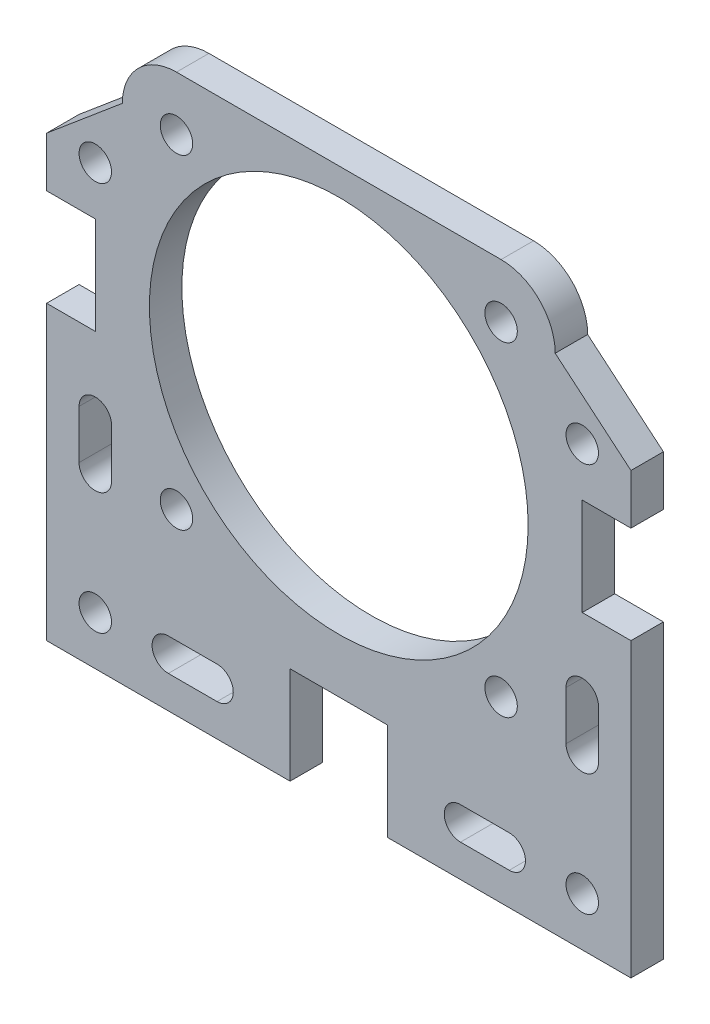
SolidWorks part; units mm, degrees
ref_plane "Alzado" through (0, 0, 0) normal (0, 0, 1) x (1, 0, 0)
ref_plane "Planta" through (0, 0, 0) normal (0, 1, 0) x (1, 0, 0)
ref_plane "Vista lateral" through (0, 0, 0) normal (1, 0, 0) x (0, 0, -1)
sketch "Model" plane through (0, 0, 0) normal (0, 0, 1) x (1, 0, 0)
  line L0 (119.29, 223.6517) -> (119.29, 219.0361)
  line L1 (119.29, 219.0361) -> (123.79, 219.0361)
  line L2 (123.79, 219.0361) -> (123.79, 210.0361)
  line L3 (123.79, 210.0361) -> (119.29, 210.0361)
  line L4 (119.29, 210.0361) -> (119.29, 183.0361)
  line L5 (119.29, 183.0361) -> (141.79, 183.0361)
  line L6 (141.79, 183.0361) -> (141.79, 192.0361)
  line L7 (141.79, 192.0361) -> (150.79, 192.0361)
  line L8 (150.79, 192.0361) -> (150.79, 183.0361)
  line L9 (150.79, 183.0361) -> (173.29, 183.0361)
  line L10 (173.29, 183.0361) -> (173.29, 210.0361)
  line L11 (173.29, 210.0361) -> (168.79, 210.0361)
  line L12 (168.79, 210.0361) -> (168.79, 219.0361)
  line L13 (168.79, 219.0361) -> (173.29, 219.0361)
  line L14 (173.29, 219.0361) -> (173.29, 223.6517)
  line L15 (173.29, 223.6517) -> (166.29, 229.5361)
  line L16 (161.29, 234.5361) -> (131.29, 234.5361)
  line L17 (126.29, 229.5361) -> (119.29, 223.6517)
  line L18 (122.29, 203.2861) -> (122.29, 198.7861)
  line L19 (125.29, 198.7861) -> (125.29, 203.2861)
  line L20 (167.29, 203.2861) -> (167.29, 198.7861)
  line L21 (170.29, 198.7861) -> (170.29, 203.2861)
  line L22 (162.04, 189.0361) -> (157.54, 189.0361)
  line L23 (157.54, 186.0361) -> (162.04, 186.0361)
  line L24 (135.04, 186.0361) -> (130.54, 186.0361)
  line L25 (130.54, 189.0361) -> (135.04, 189.0361)
  circle A0 centre (146.29, 214.5361) radius 17.5
  circle A1 centre (168.79, 223.5361) radius 1.5
  circle A2 centre (161.29, 229.5361) radius 1.5
  circle A3 centre (168.79, 187.5361) radius 1.5
  circle A4 centre (161.29, 199.5361) radius 1.5
  circle A5 centre (123.79, 223.5361) radius 1.5
  circle A6 centre (131.29, 229.5361) radius 1.5
  circle A7 centre (131.29, 199.5361) radius 1.5
  circle A8 centre (123.79, 187.5361) radius 1.5
  arc A9 (166.29, 229.5361) -> (161.29, 234.5361) centre (161.29, 229.5361) ccw
  arc A10 (131.29, 234.5361) -> (126.29, 229.5361) centre (131.29, 229.5361) ccw
  arc A11 (170.29, 203.2861) -> (167.29, 203.2861) centre (168.79, 203.2861) ccw
  arc A12 (167.29, 198.7861) -> (170.29, 198.7861) centre (168.79, 198.7861) ccw
  arc A13 (157.54, 189.0361) -> (157.54, 186.0361) centre (157.54, 187.5361) ccw
  arc A14 (162.04, 186.0361) -> (162.04, 189.0361) centre (162.04, 187.5361) ccw
  arc A15 (135.04, 186.0361) -> (135.04, 189.0361) centre (135.04, 187.5361) ccw
  arc A16 (130.54, 189.0361) -> (130.54, 186.0361) centre (130.54, 187.5361) ccw
  arc A17 (125.29, 203.2861) -> (122.29, 203.2861) centre (123.79, 203.2861) ccw
  arc A18 (122.29, 198.7861) -> (125.29, 198.7861) centre (123.79, 198.7861) ccw
extrude "Saliente-Extruir1" add sketch "Model" along normal blind 3
